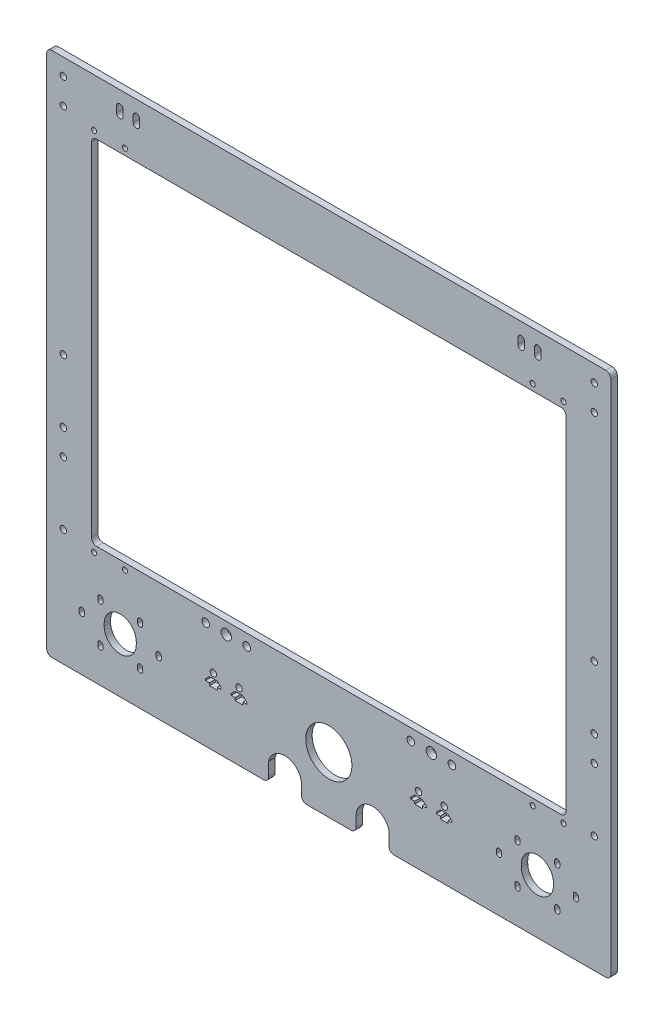
SolidWorks part; units mm, degrees
ref_plane "Front Plane" through (0, 0, 0) normal (0, 0, 1) x (1, 0, 0)
ref_plane "Top Plane" through (0, 0, 0) normal (0, 1, 0) x (1, 0, 0)
ref_plane "Right Plane" through (0, 0, 0) normal (1, 0, 0) x (0, 0, -1)
ref_plane "Plane1" through (0, 0, 0) normal (0, 0, -1) x (-1, 0, 0)
sketch "Sketch1" plane through (0, 0, 0) normal (0, 0, -1) x (-1, 0, 0)
  line L0 (317.464, -305.7433) -> (317.464, 96.2567)
  line L1 (313.464, 100.2567) -> (-118.536, 100.2567)
  line L2 (-122.536, 96.2567) -> (-122.536, -305.7433)
  line L3 (-118.536, -309.7433) -> (313.464, -309.7433)
  line L4 (-83.536, 57.7567) -> (278.464, 57.7567)
  line L5 (282.464, 53.7567) -> (282.464, -213.2433)
  line L6 (278.464, -217.2433) -> (-83.536, -217.2433)
  line L7 (-87.536, -213.2433) -> (-87.536, 53.7567)
  line L12 (97.464, -217.2433) -> (97.464, -250.7433) construction
  line L13 (97.464, 100.2567) -> (97.464, 57.7567) construction
  line L14 (-65.536, 85.7567) -> (-65.536, 88.2567) construction
  line L15 (-68.036, 85.7567) -> (-68.036, 88.2567)
  line L16 (-63.036, 85.7567) -> (-63.036, 88.2567)
  line L17 (-52.536, 85.7567) -> (-52.536, 88.2567) construction
  line L18 (-55.036, 85.7567) -> (-55.036, 88.2567)
  line L19 (-50.036, 85.7567) -> (-50.036, 88.2567)
  line L20 (247.464, 85.7567) -> (247.464, 88.2567) construction
  line L21 (244.964, 85.7567) -> (244.964, 88.2567)
  line L22 (249.964, 85.7567) -> (249.964, 88.2567)
  line L23 (260.464, 85.7567) -> (260.464, 88.2567) construction
  line L24 (257.964, 85.7567) -> (257.964, 88.2567)
  line L25 (262.964, 85.7567) -> (262.964, 88.2567)
  line L26 (-65.536, 85.7567) -> (-65.536, 83.2567) construction
  line L27 (-63.036, 85.7567) -> (-63.036, 83.2567)
  line L28 (-68.036, 85.7567) -> (-68.036, 83.2567)
  line L29 (-52.536, 85.7567) -> (-52.536, 83.2567) construction
  line L30 (-50.036, 85.7567) -> (-50.036, 83.2567)
  line L31 (-55.036, 85.7567) -> (-55.036, 83.2567)
  line L32 (247.464, 85.7567) -> (247.464, 83.2567) construction
  line L33 (249.964, 85.7567) -> (249.964, 83.2567)
  line L34 (244.964, 85.7567) -> (244.964, 83.2567)
  line L35 (260.464, 85.7567) -> (260.464, 83.2567) construction
  line L36 (262.964, 85.7567) -> (262.964, 83.2567)
  line L37 (257.964, 85.7567) -> (257.964, 83.2567)
  arc A0 (317.464, 96.2567) -> (313.464, 100.2567) centre (313.464, 96.2567) ccw
  arc A1 (-118.536, 100.2567) -> (-122.536, 96.2567) centre (-118.536, 96.2567) ccw
  arc A2 (-122.536, -305.7433) -> (-118.536, -309.7433) centre (-118.536, -305.7433) ccw
  arc A3 (313.464, -309.7433) -> (317.464, -305.7433) centre (313.464, -305.7433) ccw
  circle A4 centre (304.464, 87.2567) radius 2.5
  circle A5 centre (304.464, 67.2567) radius 2.5
  circle A6 centre (304.464, -149.7433) radius 2.5
  circle A7 centre (304.464, -169.7433) radius 2.5
  circle A8 centre (-109.536, 87.2567) radius 2.5
  circle A9 centre (-109.536, 67.2567) radius 2.5
  circle A10 centre (-109.536, -149.7433) radius 2.5
  circle A11 centre (-109.536, -169.7433) radius 2.5
  circle A12 centre (7.464, -257.2433) radius 2.5
  circle A13 centre (27.464, -257.2433) radius 2.5
  circle A14 centre (167.464, -257.2433) radius 2.5
  circle A15 centre (187.464, -257.2433) radius 2.5
  circle A16 centre (97.464, -265.7433) radius 18
  circle A17 centre (17.464, -226.2433) radius 4.05
  circle A18 centre (161.464, -226.2433) radius 3
  circle A19 centre (33.464, -226.2433) radius 3
  circle A20 centre (1.464, -226.2433) radius 3
  circle A21 centre (177.464, -226.2433) radius 4.05
  circle A22 centre (193.464, -226.2433) radius 3
  circle A24 centre (-85.536, 62.7567) radius 2
  circle A25 centre (-61.536, 62.7567) radius 2
  circle A27 centre (256.464, 62.7567) radius 2
  circle A28 centre (280.464, 62.7567) radius 2
  circle A30 centre (-85.536, -222.2433) radius 2
  circle A31 centre (-61.536, -222.2433) radius 2
  circle A33 centre (256.464, -222.2433) radius 2
  circle A34 centre (280.464, -222.2433) radius 2
  arc A35 (278.464, 57.7567) -> (282.464, 53.7567) centre (278.464, 53.7567) cw
  arc A36 (282.464, -213.2433) -> (278.464, -217.2433) centre (278.464, -213.2433) cw
  arc A37 (-83.536, -217.2433) -> (-87.536, -213.2433) centre (-83.536, -213.2433) cw
  arc A38 (-87.536, 53.7567) -> (-83.536, 57.7567) centre (-83.536, 53.7567) cw
  circle A41 centre (-65.186, -266.2433) radius 12.5
  circle A42 centre (-80.686, -250.7433) radius 2
  circle A43 centre (-49.686, -250.7433) radius 2
  circle A44 centre (-49.686, -281.7433) radius 2
  circle A45 centre (-80.686, -281.7433) radius 2
  circle A46 centre (290.114, -266.2433) radius 2
  circle A47 centre (230.114, -266.2433) radius 2
  circle A48 centre (275.614, -281.7433) radius 2
  circle A49 centre (244.614, -281.7433) radius 2
  circle A50 centre (244.614, -250.7433) radius 2
  arc A52 (-68.036, 83.2567) -> (-63.036, 83.2567) centre (-65.536, 83.2567) ccw
  circle A57 centre (-35.186, -266.2433) radius 2
  circle A58 centre (-95.186, -266.2433) radius 2
  circle A59 centre (275.614, -250.7433) radius 2
  circle A60 centre (260.114, -266.2433) radius 12.5
  arc A62 (-63.036, 88.2567) -> (-68.036, 88.2567) centre (-65.536, 88.2567) ccw
  arc A64 (-50.036, 88.2567) -> (-55.036, 88.2567) centre (-52.536, 88.2567) ccw
  arc A66 (249.964, 88.2567) -> (244.964, 88.2567) centre (247.464, 88.2567) ccw
  arc A68 (262.964, 88.2567) -> (257.964, 88.2567) centre (260.464, 88.2567) ccw
  arc A70 (-55.036, 83.2567) -> (-50.036, 83.2567) centre (-52.536, 83.2567) ccw
  arc A72 (244.964, 83.2567) -> (249.964, 83.2567) centre (247.464, 83.2567) ccw
  arc A74 (257.964, 83.2567) -> (262.964, 83.2567) centre (260.464, 83.2567) ccw
  point P113 (-65.536, 84.5067)
  point P138 (-65.536, 87.0067)
  point P144 (-52.536, 87.0067)
  point P151 (247.464, 84.5067)
  point P152 (247.464, 87.0067)
  point P158 (260.464, 87.0067)
  point P165 (-52.536, 84.5067)
  point P173 (260.464, 84.5067)
  dimension "D2" = 4
  dimension "D4" = 31
  dimension "D6" = 31
  dimension "D7" = 25
  dimension "D8" = 43.5
  dimension "D9" = 57.35
  dimension "D10" = 42.5
  dimension "D11" = 43.5
  dimension "D12" = 4
  dimension "D13" = 4
  dimension "D14" = 4
  dimension "D15" = 4
  dimension "D16" = 4
  dimension "D17" = 15.5
  dimension "D18" = 15.5
  dimension "D19" = 15.5
  dimension "D20" = 15.5
  dimension "D21" = 30
  dimension "D22" = 14.5
  dimension "D24" = 275
  dimension "D26" = 440
  dimension "D27" = 36
  dimension "D28" = 44
  dimension "D1" = 31
  dimension "D3" = 60
  dimension "D5" = 31
  dimension "D23" = 70
  dimension "D25" = 92.5
  dimension "D30" = 35
  dimension "D31" = 35
  dimension "D32" = 402
extrude "Boss-Extrude1" add sketch "Sketch1" against normal blind 5
sketch "Sketch4" plane through (0, 0, 5) normal (0, 0, 1) x (1, 0, 0)
  line L0 (-76.214, -298.1933) -> (-76.214, -309.7433)
  line L1 (-76.214, -309.7433) -> (-50.547, -309.7433)
  line L2 (-50.547, -295.2701) -> (-50.547, -309.7433)
  line L3 (-97.464, -292.7433) -> (-97.464, -309.7433) construction
  line L4 (-144.3811, -295.2701) -> (-144.3811, -309.7433)
  line L5 (-118.714, -309.7433) -> (-144.3811, -309.7433)
  line L6 (-118.714, -298.1933) -> (-118.714, -309.7433)
  arc A0 (-50.547, -295.2701) -> (-76.214, -298.1933) centre (-63.214, -298.1933) ccw
  arc A1 (-144.3811, -295.2701) -> (-118.714, -298.1933) centre (-131.714, -298.1933) cw
sketch "Sketch5" plane through (0, 0, 5) normal (0, 0, 1) x (1, 0, 0)
  line L0 (-275.614, -250.7433) -> (-275.614, -252.7433) construction
  line L1 (-273.614, -250.7433) -> (-273.614, -252.7433)
  line L2 (-277.614, -250.7433) -> (-277.614, -252.7433)
  line L3 (-260.114, -266.2433) -> (-260.114, -268.2433) construction
  line L4 (-247.614, -266.2433) -> (-247.614, -268.2433)
  line L5 (-272.614, -266.2433) -> (-272.614, -268.2433)
  line L6 (-290.114, -266.2433) -> (-290.114, -268.2433) construction
  line L7 (-288.114, -266.2433) -> (-288.114, -268.2433)
  line L8 (-292.114, -266.2433) -> (-292.114, -268.2433)
  line L9 (-275.614, -281.7433) -> (-275.614, -283.7433) construction
  line L10 (-273.614, -281.7433) -> (-273.614, -283.7433)
  line L11 (-277.614, -281.7433) -> (-277.614, -283.7433)
  line L12 (-244.614, -281.7433) -> (-244.614, -283.7433) construction
  line L13 (-242.614, -281.7433) -> (-242.614, -283.7433)
  line L14 (-246.614, -281.7433) -> (-246.614, -283.7433)
  line L15 (-230.114, -266.2433) -> (-230.114, -268.2433) construction
  line L16 (-228.114, -266.2433) -> (-228.114, -268.2433)
  line L17 (-232.114, -266.2433) -> (-232.114, -268.2433)
  line L18 (-244.614, -250.7433) -> (-244.614, -252.7433) construction
  line L19 (-242.614, -250.7433) -> (-242.614, -252.7433)
  line L20 (-246.614, -250.7433) -> (-246.614, -252.7433)
  circle A0 centre (-275.614, -250.7433) radius 2 construction
  arc A1 (-273.614, -250.7433) -> (-277.614, -250.7433) centre (-275.614, -250.7433) ccw
  arc A2 (-277.614, -252.7433) -> (-273.614, -252.7433) centre (-275.614, -252.7433) ccw
  arc A3 (-247.614, -266.2433) -> (-272.614, -266.2433) centre (-260.114, -266.2433) ccw
  arc A4 (-272.614, -268.2433) -> (-247.614, -268.2433) centre (-260.114, -268.2433) ccw
  circle A5 centre (-260.114, -266.2433) radius 12.5 construction
  circle A6 centre (-290.114, -266.2433) radius 2 construction
  arc A7 (-288.114, -266.2433) -> (-292.114, -266.2433) centre (-290.114, -266.2433) ccw
  arc A8 (-292.114, -268.2433) -> (-288.114, -268.2433) centre (-290.114, -268.2433) ccw
  circle A9 centre (-275.614, -281.7433) radius 2 construction
  arc A10 (-273.614, -281.7433) -> (-277.614, -281.7433) centre (-275.614, -281.7433) ccw
  arc A11 (-277.614, -283.7433) -> (-273.614, -283.7433) centre (-275.614, -283.7433) ccw
  circle A12 centre (-244.614, -281.7433) radius 2 construction
  arc A13 (-242.614, -281.7433) -> (-246.614, -281.7433) centre (-244.614, -281.7433) ccw
  arc A14 (-246.614, -283.7433) -> (-242.614, -283.7433) centre (-244.614, -283.7433) ccw
  circle A15 centre (-230.114, -266.2433) radius 2 construction
  arc A16 (-228.114, -266.2433) -> (-232.114, -266.2433) centre (-230.114, -266.2433) ccw
  arc A17 (-232.114, -268.2433) -> (-228.114, -268.2433) centre (-230.114, -268.2433) ccw
  circle A18 centre (-244.614, -250.7433) radius 2 construction
  arc A19 (-242.614, -250.7433) -> (-246.614, -250.7433) centre (-244.614, -250.7433) ccw
  arc A20 (-246.614, -252.7433) -> (-242.614, -252.7433) centre (-244.614, -252.7433) ccw
  point P4 (-275.614, -251.7433)
  point P9 (-260.114, -267.2433)
  point P22 (-290.114, -267.2433)
  point P27 (-275.614, -282.7433)
  point P36 (-244.614, -282.7433)
  point P45 (-230.114, -267.2433)
  point P54 (-244.614, -251.7433)
  dimension "D1" = 2
  dimension "D2" = 2
  dimension "D3" = 0
extrude "Cut-Extrude1" cut sketch "Sketch4" against normal blind 14
extrude "Cut-Extrude2" cut sketch "Sketch5" against normal blind 14
ref_plane "Plane2" through (-97.464, 0, 0) normal (1, 0, 0) x (0, 0, -1)
mirror "Mirror1" about plane through (-97.464, 0, 0) normal (1, 0, 0) of "Cut-Extrude2"
fillet "Fillet1" radius 4 4 edges at (-50.547, -309.7433, 2.5) (-76.214, -309.7433, 2.5) (-118.714, -309.7433, 2.5) (-144.3811, -309.7433, 2.5)
sketch "Sketch6" plane through (0, 0, 0) normal (0, 0, -1) x (-1, 0, 0)
  line L25 (13.5751, -264.2019) -> (10.5165, -261.1433)
  line L26 (10.5165, -261.1433) -> (4.4339, -261.1432)
  line L27 (4.4339, -261.1432) -> (1.3751, -264.2019)
  line L28 (1.3751, -265.3433) -> (1.3751, -264.2019)
  line L29 (13.5751, -265.3433) -> (10.5165, -265.3433)
  line L30 (13.5751, -265.3433) -> (13.5751, -264.2019)
  line L31 (33.5751, -264.2019) -> (30.5165, -261.1433)
  line L32 (30.5165, -261.1433) -> (24.4339, -261.1432)
  line L33 (24.4339, -261.1432) -> (21.3751, -264.2019)
  line L34 (21.3751, -265.3433) -> (21.3751, -264.2019)
  line L35 (33.5751, -265.3433) -> (30.5165, -265.3433)
  line L36 (33.5751, -265.3433) -> (33.5751, -264.2019)
  line L37 (173.5751, -264.2019) -> (170.5165, -261.1433)
  line L38 (170.5165, -261.1433) -> (164.4339, -261.1432)
  line L39 (164.4339, -261.1432) -> (161.3751, -264.2019)
  line L40 (161.3751, -265.3433) -> (161.3751, -264.2019)
  line L41 (173.5751, -265.3433) -> (170.5165, -265.3433)
  line L42 (173.5751, -265.3433) -> (173.5751, -264.2019)
  line L43 (193.5751, -264.2019) -> (190.5165, -261.1433)
  line L44 (190.5165, -261.1433) -> (184.4339, -261.1432)
  line L45 (184.4339, -261.1432) -> (181.3751, -264.2019)
  line L46 (181.3751, -265.3433) -> (181.3751, -264.2019)
  line L47 (193.5751, -265.3433) -> (190.5165, -265.3433)
  line L48 (193.5751, -265.3433) -> (193.5751, -264.2019)
  line L49 (24.4339, -265.3433) -> (21.3751, -265.3433)
  line L51 (4.4339, -265.3433) -> (4.4339, -267.3433)
  line L52 (4.4339, -267.3433) -> (10.5165, -267.3433)
  line L53 (10.5165, -265.3433) -> (10.5165, -267.3433)
  line L55 (24.4339, -265.3433) -> (24.4339, -267.3433)
  line L56 (24.4339, -267.3433) -> (30.5165, -267.3433)
  line L57 (30.5165, -265.3433) -> (30.5165, -267.3433)
  line L58 (1.3751, -265.3433) -> (4.4339, -265.3433)
  line L59 (164.4339, -265.3433) -> (161.3751, -265.3433)
  line L61 (164.4339, -265.3433) -> (164.4339, -267.3433)
  line L62 (164.4339, -267.3433) -> (170.5165, -267.3433)
  line L63 (170.5165, -265.3433) -> (170.5165, -267.3433)
  line L64 (184.4339, -265.3433) -> (181.3751, -265.3433)
  line L71 (184.4339, -265.3433) -> (184.4339, -267.3433)
  line L72 (184.4339, -267.3433) -> (190.5165, -267.3433)
  line L73 (190.5165, -265.3433) -> (190.5165, -267.3433)
  circle A0 centre (7.464, -257.2433) radius 2.5 construction
  dimension "D2" = 2
  dimension "D4" = 8.1
  dimension "D1" = 2
  dimension "D3" = 3.9
extrude "Cut-Extrude3" cut sketch "Sketch6" against normal blind 10
sketch "Sketch7" plane through (0, 0, 0) normal (0, 0, -1) x (-1, 0, 0)
  line L0 (-109.536, -149.7433) -> (-109.536, -169.7433) construction
  line L1 (-109.536, -159.7433) -> (-109.536, -100.7433) construction
  line L2 (97.464, -247.7433) -> (97.464, -283.7433) construction
  line L3 (304.464, -159.7433) -> (304.464, -100.7433) construction
  line L4 (304.464, -149.7433) -> (304.464, -169.7433) construction
  circle A0 centre (-109.536, -100.7433) radius 2.5
  circle A1 centre (97.464, -265.7433) radius 18 construction
  circle A2 centre (-109.536, -218.7433) radius 2.5
  circle A3 centre (304.464, -218.7433) radius 2.5
  circle A4 centre (304.464, -100.7433) radius 2.5
  dimension "D1" = 2
  dimension "D2" = 5
extrude "Cut-Extrude4" cut sketch "Sketch7" against normal blind 10
